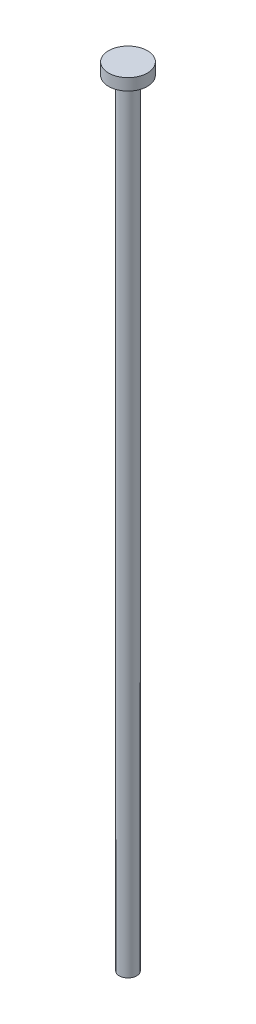
SolidWorks part; units mm, degrees
ref_plane "Front Plane" through (0, 0, 0) normal (0, 0, 1) x (1, 0, 0)
ref_plane "Top Plane" through (0, 0, 0) normal (0, 1, 0) x (1, 0, 0)
ref_plane "Right Plane" through (0, 0, 0) normal (1, 0, 0) x (0, 0, -1)
sketch "Sketch1" plane through (0, 0, 0) normal (0, 1, 0) x (1, 0, 0)
  circle A0 centre (0, 0) radius 2.25
  dimension "D1" = 4.5
extrude "Boss-Extrude1" add sketch "Sketch1" along normal mid plane 200
sketch "Sketch2" plane through (0, 100, 0) normal (0, 1, 0) x (1, 0, 0)
  circle A0 centre (0, 0) radius 5
  dimension "D1" = 5
extrude "Boss-Extrude2" add sketch "Sketch2" along normal blind 3
